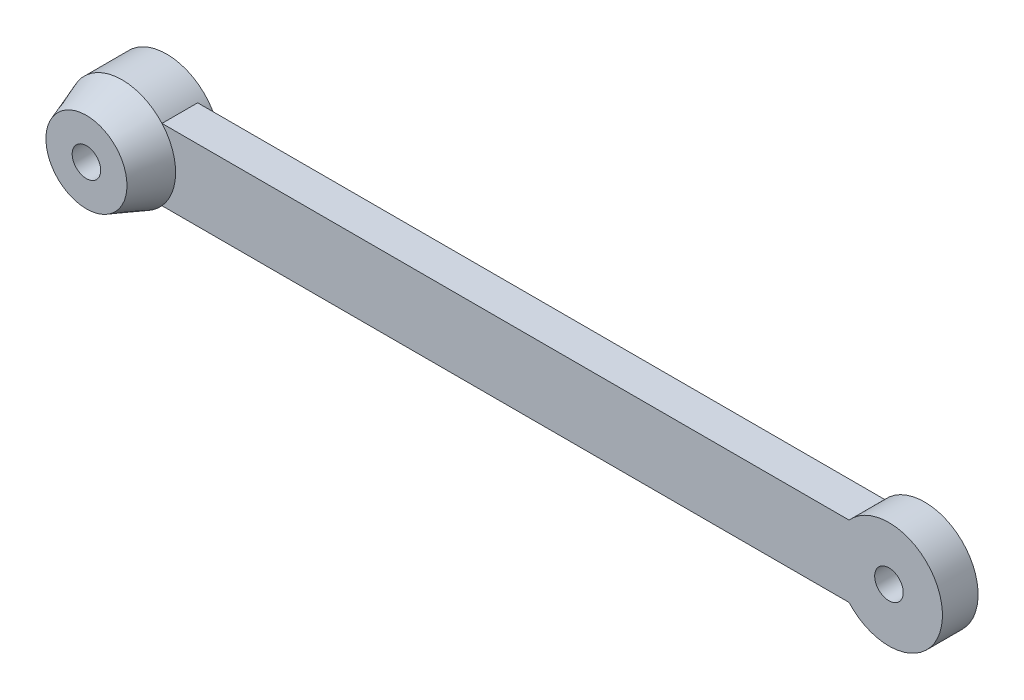
SolidWorks part; units mm, degrees
ref_plane "Ön Düzlem" through (0, 0, 0) normal (0, 0, 1) x (1, 0, 0)
ref_plane "Üst Düzlem" through (0, 0, 0) normal (0, 1, 0) x (1, 0, 0)
ref_plane "Sağ Düzlem" through (0, 0, 0) normal (1, 0, 0) x (0, 0, -1)
sketch "Sketch1" plane through (0, 0, 0) normal (0, 0, 1) x (1, 0, 0)
  line L0 (8.2916, 12.5) -> (206.7084, 12.5)
  line L1 (8.2916, -12.5) -> (206.7084, -12.5)
  circle A0 centre (0, 0) radius 15
  circle A1 centre (215, 0) radius 15
  dimension "D1" = 30
  dimension "D3" = 30
  dimension "D2" = 25
  dimension "D4" = 215
  dimension "D5" = 12.5
extrude "Boss-Extrude1" add sketch "Sketch1" along normal blind 10 contours A0 | A1
sketch "Sketch2" plane through (0, 0, 10) normal (0, 0, 1) x (1, 0, 0)
  circle A1 centre (0, 0) radius 15
  circle A2 centre (0, 0) radius 15
  dimension "D1" = 0
extrude "Boss-Extrude2" add sketch "Sketch2" along normal blind 10 draft 20
sketch "Sketch5" plane through (0, 0, 0) normal (0, 0, 1) x (1, 0, 0)
  line L0 (11.1803, 10) -> (203.8197, 10)
  line L1 (203.8197, -10) -> (11.1803, -10)
  circle A0 centre (0, 0) radius 15 construction
  circle A1 centre (215, 0) radius 15 construction
  circle A2 centre (0, 0) radius 15
  circle A3 centre (215, 0) radius 15
  dimension "D1" = 20
  dimension "D2" = 10
extrude "Boss-Extrude3" add sketch "Sketch5" along normal blind 5 contours A3 L0 A2 L1
sketch "Sketch6" plane through (0, 0, 5) normal (0, 0, 1) x (1, 0, 0)
  circle A1 centre (0, 0) radius 15 construction
  arc A3 (14.7902, -2.5) -> (14.7902, 2.5) centre (0, 0) ccw
extrude "Boss-Extrude4" add sketch "Sketch6" along normal blind 5
sketch "Sketch13" plane through (0, 0, 0) normal (0, 0, -1) x (-1, 0, 0)
  circle A0 centre (-215, 0) radius 4
  circle A1 centre (0, 0) radius 4
extrude "Cut-Extrude1" cut sketch "Sketch13" against normal blind 20
sketch "Sketch14" plane through (0, 0, 0) normal (0, 0, -1) x (-1, 0, 0)
  circle A0 centre (0, 0) radius 4
  circle A1 centre (0, 0) radius 15
extrude "Boss-Extrude7" add sketch "Sketch14" along normal blind 2.5
